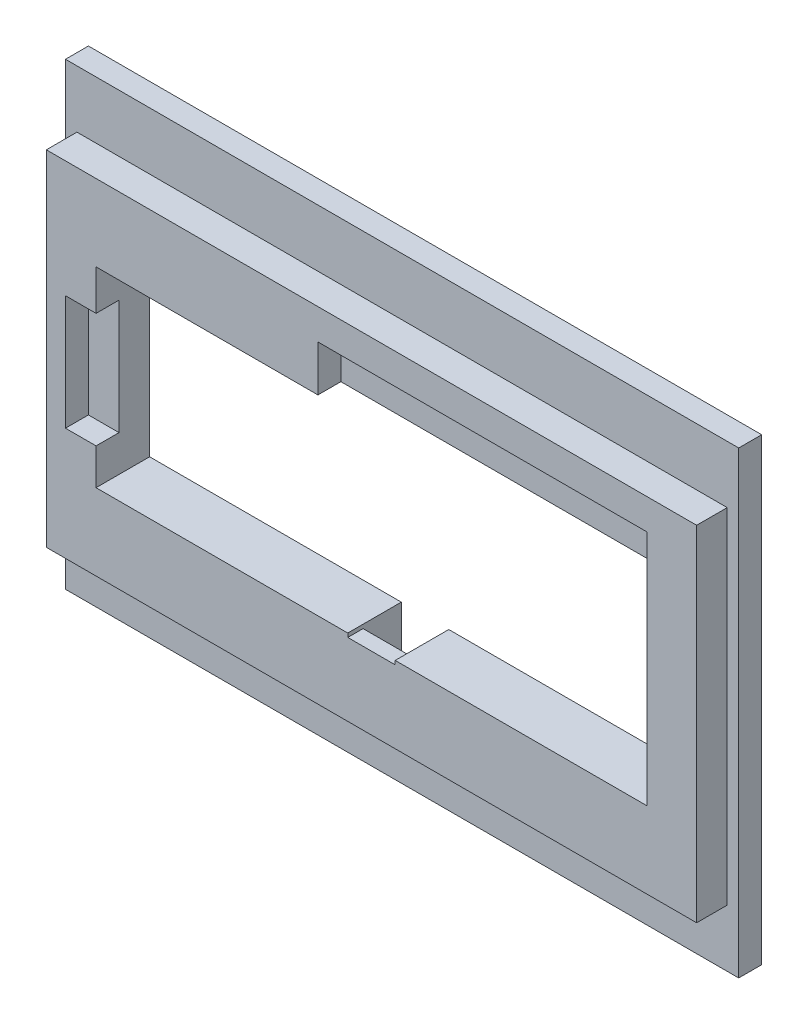
SolidWorks part; units mm, degrees
ref_plane "Front Plane" through (0, 0, 0) normal (0, 0, 1) x (1, 0, 0)
ref_plane "Top Plane" through (0, 0, 0) normal (0, 1, 0) x (1, 0, 0)
ref_plane "Right Plane" through (0, 0, 0) normal (1, 0, 0) x (0, 0, -1)
sketch "Sketch5" plane through (0, 0, 0) normal (0, 0, 1) x (1, 0, 0)
  line L0 (-36, -12.5) -> (-36, 12.5)
  line L1 (-36, -12.5) -> (36, -12.5)
  line L2 (-36, 12.5) -> (36, 12.5)
  line L3 (36, -12.5) -> (36, 12.5)
  line L4 (-36, -12.5) -> (36, 12.5) construction
  line L5 (-36, 12.5) -> (36, -12.5) construction
  line L7 (-42.5, -22.5) -> (42.5, -22.5)
  line L8 (-42.5, -22.5) -> (-42.5, 22.5)
  line L9 (-42.5, 22.5) -> (42.5, 22.5)
  line L10 (42.5, -22.5) -> (42.5, 22.5)
  line L11 (-42.5, -22.5) -> (42.5, 22.5) construction
  line L12 (-42.5, 22.5) -> (42.5, -22.5) construction
  point P0 (0, 0)
  point P1 (0, 0)
  dimension "D1" = 72
  dimension "D2" = 25
  dimension "D3" = 85
  dimension "D4" = 45
extrude "Boss-Extrude3" add sketch "Sketch5" along normal blind 4
sketch "Sketch10" plane through (0, 0, 0) normal (0, 0, -1) x (-1, 0, 0)
  line L1 (-44, -30) -> (44, -30)
  line L2 (-44, -30) -> (-44, 30)
  line L3 (-44, 30) -> (44, 30)
  line L4 (44, -30) -> (44, 30)
  line L5 (-44, -30) -> (44, 30) construction
  line L6 (-44, 30) -> (44, -30) construction
  line L7 (-36, -12.5) -> (36, -12.5)
  line L8 (-36, -12.5) -> (-36, 12.5)
  line L9 (-36, 12.5) -> (36, 12.5)
  line L10 (36, -12.5) -> (36, 12.5)
  line L11 (-36, -12.5) -> (36, 12.5) construction
  line L12 (-36, 12.5) -> (36, -12.5) construction
  point P0 (0, 0)
  point P6 (0, 0)
  dimension "D1" = 88
  dimension "D2" = 60
extrude "Boss-Extrude4" add sketch "Sketch10" along normal blind 3
sketch "Sketch12" plane through (0, 0, 4) normal (0, 0, 1) x (1, 0, 0)
  line L0 (-36, 12.5) -> (-36, -12.5) construction
  line L1 (-36, 7.2355) -> (-40, 7.2355)
  line L2 (-36, 7.2355) -> (-36, -7.7645)
  line L3 (-36, -7.7645) -> (-40, -7.7645)
  line L4 (-40, 7.2355) -> (-40, -7.7645)
  dimension "D1" = 15
  dimension "D2" = 4
extrude "Cut-Extrude6" cut sketch "Sketch12" against normal blind 3
sketch "Sketch13" plane through (0, 0, 4) normal (0, 0, 1) x (1, 0, 0)
  line L1 (36, 12.5) -> (-7, 12.5)
  line L2 (36, 12.5) -> (36, 18.5)
  line L3 (36, 18.5) -> (-7, 18.5)
  line L4 (-7, 12.5) -> (-7, 18.5)
  dimension "D1" = 6
  dimension "D2" = 43
extrude "Cut-Extrude7" cut sketch "Sketch13" against normal blind 3
sketch "Sketch18" plane through (0, -12.5, 0) normal (0, 1, 0) x (1, 0, 0)
  line L0 (36, 3) -> (-36, 3) construction
  line L1 (-3.1, 3) -> (3.1, 3)
  line L2 (-3.1, 3) -> (-3.1, -2)
  line L3 (-3.1, -2) -> (3.1, -2)
  line L4 (3.1, 3) -> (3.1, -2)
  line L5 (-3.1, 3) -> (3.1, -2) construction
  line L6 (-3.1, -2) -> (3.1, 3) construction
  point P0 (0, 0)
  point P10 (0, 0.5)
  dimension "D1" = 5
  dimension "D2" = 6.2
extrude "Cut-Extrude10" cut sketch "Sketch18" against normal blind 9
sketch "Sketch19" plane through (0, 0, 2) normal (0, 0, -1) x (-1, 0, 0)
  line L0 (-3.1, -21.5) -> (-3.1, -12.5) construction
  line L1 (3.1, -12.5) -> (-3.1, -12.5)
  line L2 (3.1, -12.5) -> (3.1, -13)
  line L3 (3.1, -13) -> (-3.1, -13)
  line L4 (-3.1, -12.5) -> (-3.1, -13)
  dimension "D1" = 0.5
extrude "Cut-Extrude11" cut sketch "Sketch19" against normal blind 10
